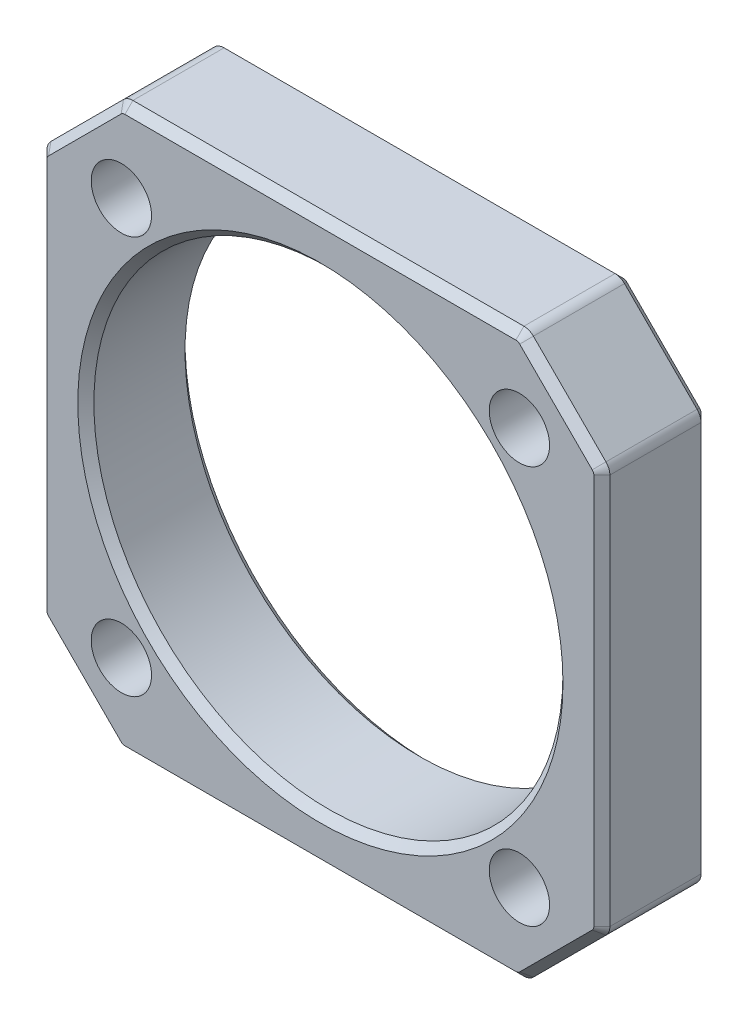
SolidWorks part; units mm, degrees
material "ABS"
ref_plane "Front Plane" through (0, 0, 0) normal (0, 0, 1) x (1, 0, 0)
ref_plane "Top Plane" through (0, 0, 0) normal (0, 1, 0) x (1, 0, 0)
ref_plane "Right Plane" through (0, 0, 0) normal (1, 0, 0) x (0, 0, -1)
sketch "Sketch1" plane through (0, 0, 0) normal (0, 0, 1) x (1, 0, 0)
  line L1 (21, -21) -> (-21, -21)
  line L2 (21, -21) -> (21, 21)
  line L3 (21, 21) -> (-21, 21)
  line L4 (-21, -21) -> (-21, 21)
  line L5 (21, -21) -> (-21, 21) construction
  line L6 (21, 21) -> (-21, -21) construction
  circle A0 centre (0, 0) radius 17.5
  dimension "D1" = 35
  dimension "D2" = 42
extrude "Boss-Extrude1" add sketch "Sketch1" along normal blind 8
hole_wizard "M4 Clearance Hole1" positions "Sketch4" profile "Sketch5" hole size "M4" standard "DIN" end condition up to next
sketch "Sketch4" plane through (0, 0, 8) normal (0, 0, 1) x (1, 0, 0)
  line L0 (0, 0) -> (21, 21) construction
  circle A0 centre (0, 0) radius 21 construction
  point P0 (14.8492, 14.8492)
  dimension "D1" = 42
sketch "Sketch5" plane through (14.8492, 14.8492, 8) normal (1, 0, 0) x (0, -1, 0)
  line L0 (0, 0) -> (0, 8)
  line L1 (0, 8) -> (2.25, 8)
  line L2 (2.25, 8) -> (2.25, 0)
  line L5 (2.25, 0) -> (0, 0)
  line L11 (0, -6.35) -> (0, 107.95) construction
  dimension "Thru Hole Dia." = 4.5
  dimension "Thru Hole Depth" = 8
pattern_circular "CirPattern1" count 4 over 360 about axis through (0, 0, 0) along (0, 0, 1) of "M4 Clearance Hole1"
chamfer "Chamfer2" distance 6 angle 45 4 edges at (-21, 21, 4) (21, 21, 4) (-21, -21, 4) (21, -21, 4)
fillet "Fillet1" radius 1 8 edges at (21, -15, 4) (15, -21, 4) (-15, -21, 4) (-21, -15, 4) (-21, 15, 4) (-15, 21, 4) (15, 21, 4) (21, 15, 4)
chamfer "Chamfer1" distance 0.6 angle 45 34 edges at (17.5, 0, 0) (17.5, 0, 8) (-18, -18, 0) (0, -21, 0) (18, -18, 0) (21, 0, 0) (18, 18, 0) (0, 21, 0) (-18, 18, 0) (-21, 0, 0) (18, 18, 8) (21, 0, 8) (18, -18, 8) (0, -21, 8) (-18, -18, 8) (-21, 0, 8) (-18, 18, 8) (0, 21, 8) (20.9239, 14.9685, 0) (14.9685, 20.9239, 0) (-14.9685, 20.9239, 0) (-20.9239, 14.9685, 0) (-20.9239, -14.9685, 0) (-14.9685, -20.9239, 0) (14.9685, -20.9239, 0) (20.9239, -14.9685, 0) (14.9685, -20.9239, 8) (-14.9685, -20.9239, 8) (-20.9239, -14.9685, 8) (-20.9239, 14.9685, 8) (-14.9685, 20.9239, 8) (14.9685, 20.9239, 8) (20.9239, 14.9685, 8) (20.9239, -14.9685, 8)
